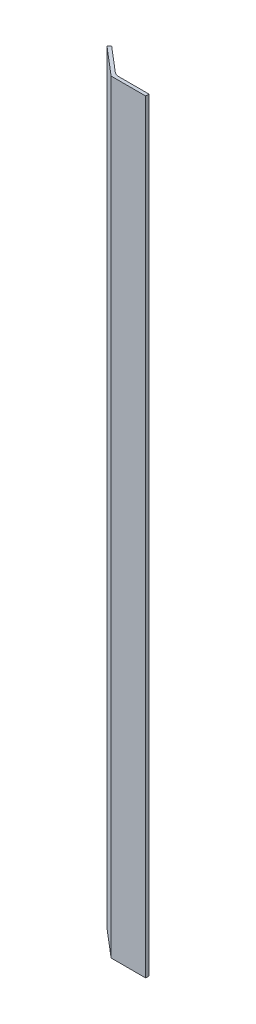
SolidWorks part; units mm, degrees
ref_plane "Спереди" through (0, 0, 0) normal (0, 0, 1) x (1, 0, 0)
ref_plane "Сверху" through (0, 0, 0) normal (0, 1, 0) x (1, 0, 0)
ref_plane "Справа" through (0, 0, 0) normal (1, 0, 0) x (0, 0, -1)
sketch "Эскиз1" plane through (0, 0, 0) normal (0, 1, 0) x (1, 0, 0)
  line L0 (-20.5084, 12.7927) -> (-19.212, 14.3155)
  line L1 (-1.1334, 0.4869) -> (17.1228, 0.4869)
  line L2 (-19.212, 14.3155) -> (-4.3752, 1.6802)
  line L3 (-20.5084, 12.7927) -> (-3.7046, -1.5131)
  line L4 (-3.7046, -1.5131) -> (17.1228, -1.5131)
  line L5 (17.1228, -1.5131) -> (17.1228, 0.4869)
  arc A0 (-1.1334, 0.4869) -> (-4.3752, 1.6802) centre (-1.1334, 5.4869) cw
  dimension "D1" = 5
extrude "Вытянуть1" add sketch "Эскиз1" along normal blind 460 from offset 40
sketch "Эскиз2" plane through (-2.3036, 0, 2.7059) normal (-0.6482, 0, 0.7614) x (0.7614, 0, 0.6482)
  line L0 (-29.699, 533.7137) -> (-29.699, 0.5) construction
  line L1 (-29.699, 310.9032) -> (-12.7057, 310.9032)
  line L2 (-29.699, 310.9032) -> (-29.699, 135.9413)
  line L3 (-29.699, 135.9413) -> (-12.7057, 135.9413)
  line L4 (-12.7057, 310.9032) -> (-12.7057, 135.9413)
extrude "Вырез-Вытянуть1" [suppressed] cut sketch "Эскиз2" against normal through all
